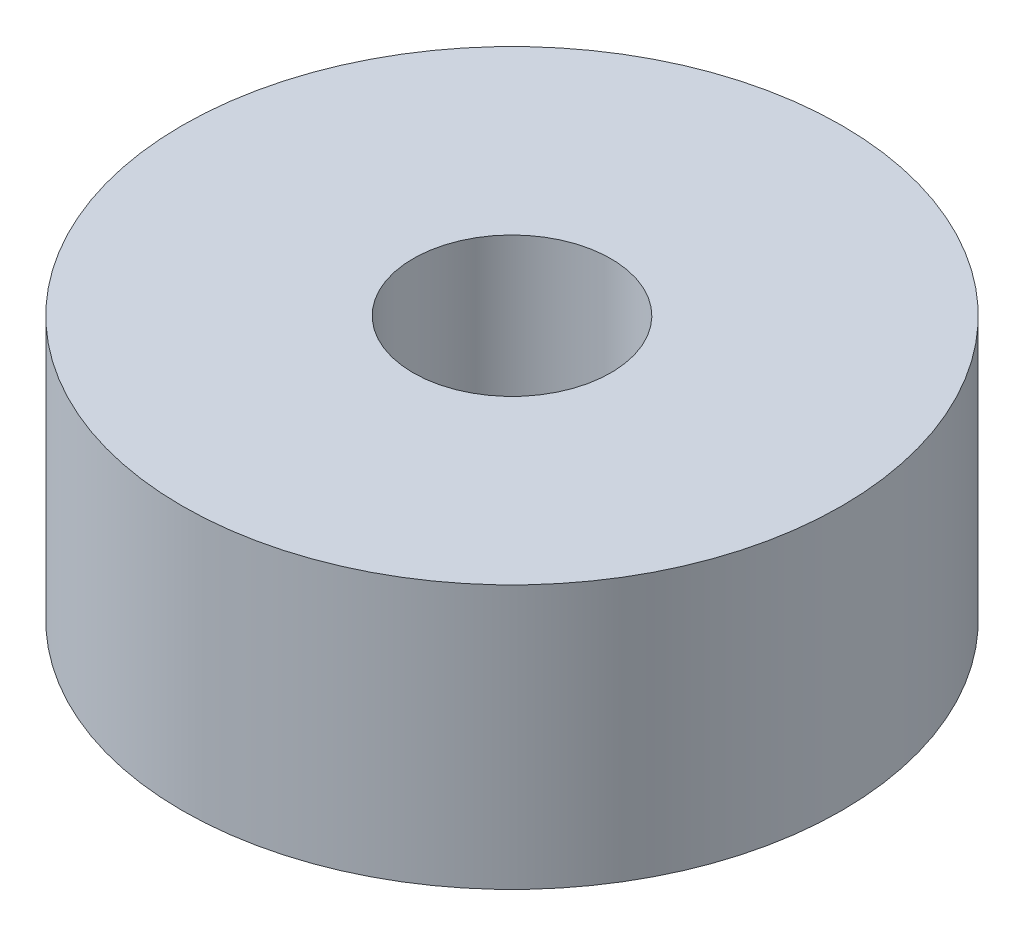
SolidWorks part; units mm, degrees
ref_plane "Front" through (0, 0, 0) normal (0, 0, 1) x (1, 0, 0)
ref_plane "Top" through (0, 0, 0) normal (0, 1, 0) x (1, 0, 0)
ref_plane "Right" through (0, 0, 0) normal (1, 0, 0) x (0, 0, -1)
sketch "Sketch1" plane through (0, 0, 0) normal (0, 1, 0) x (1, 0, 0)
  circle A0 centre (0, 0) radius 5
  circle A1 centre (0, 0) radius 1.5
  dimension "D1" = 10
  dimension "D2" = 3
extrude "Boss-Extrude1" add sketch "Sketch1" along normal blind 4
